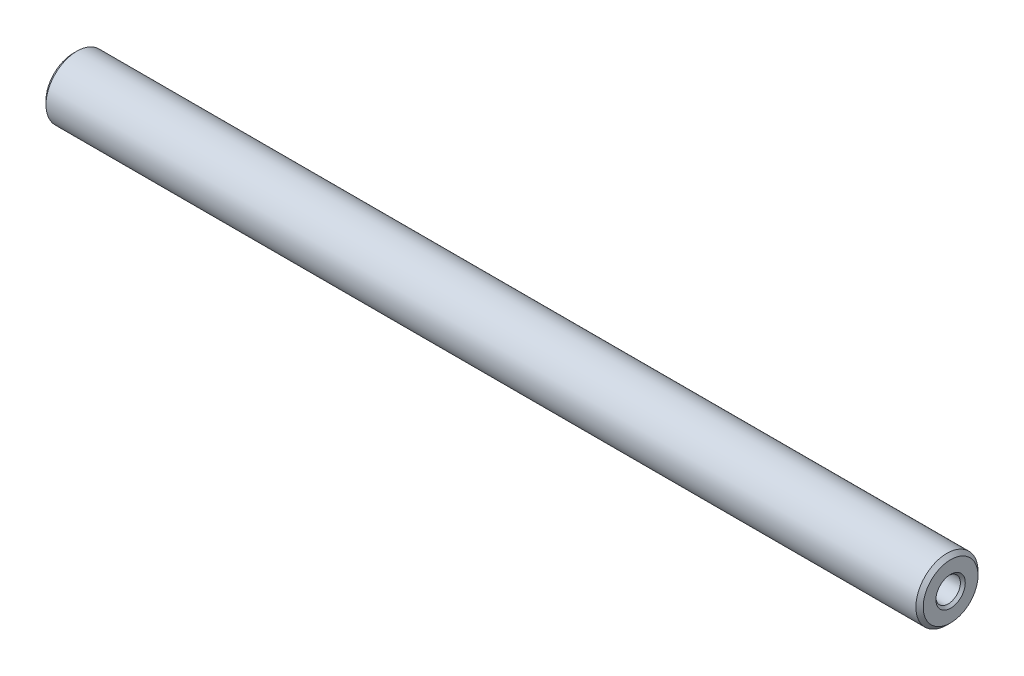
SolidWorks part; units mm, degrees
material "Plain Carbon Steel"
ref_plane "Front Plane" through (0, 0, 0) normal (0, 0, 1) x (1, 0, 0)
ref_plane "Top Plane" through (0, 0, 0) normal (0, 1, 0) x (1, 0, 0)
ref_plane "Right Plane" through (0, 0, 0) normal (1, 0, 0) x (0, 0, -1)
sketch "Sketch2" plane through (0, 0, 0) normal (1, 0, 0) x (0, 0, -1)
  circle A0 centre (0, 0) radius 12.7
  dimension "D1" = 25.4
extrude "Boss-Extrude1" add sketch "Sketch2" along normal mid plane 358.6
chamfer "Chamfer1" distance 1.5 angle 45 2 edges at (-179.3, 0, -12.7) (179.3, 0, -12.7)
hole_wizard "M10 Tapped Hole1" positions "Sketch4" profile "Sketch5" tap size "M10" standard "DIN"
sketch "Sketch4" plane through (179.3, 0, 0) normal (1, 0, 0) x (0, 0, -1)
  point P0 (0, 0)
sketch "Sketch5" plane through (179.3, 0, 0) normal (0, 1, 0) x (0, 0, -1)
  line L0 (0, 0) -> (0, 27.0537)
  line L1 (0, 27.0537) -> (4.25, 24.5)
  line L2 (4.25, 24.5) -> (4.25, 20)
  line L3 (4.25, 20) -> (5, 20)
  line L5 (5, 20) -> (5, 1)
  line L6 (5, 1) -> (6, 0)
  line L7 (6, 0) -> (0, 0)
  line L8 (-5, 1) -> (-6, 0) construction
  line L10 (0, 27.0537) -> (-4.25, 24.5) construction
  line L11 (0, -6.35) -> (0, 107.95) construction
  dimension "Tap Drill Dia." = 8.5
  dimension "Tap Drill Depth" = 24.5
  dimension "Thread Major Dia." = 10
  dimension "Thread Depth" = 20
  dimension "Near C'Sink Dia." = 12
  dimension "Near C'Sink Angle" = 90
  dimension "Drill Angle" = 118
mirror "Mirror1" about plane through (0, 0, 0) normal (1, 0, 0) of "M10 Tapped Hole1"
sketch "Sketch6" plane through (0, 0, 0) normal (0, 1, 0) x (1, 0, 0)
  line L0 (-203.3, 0) -> (203.3, 0)
  line L1 (179.3, -11.2) -> (179.3, 11.2) construction
  point P4 (0, 0)
  dimension "D1" = 24
